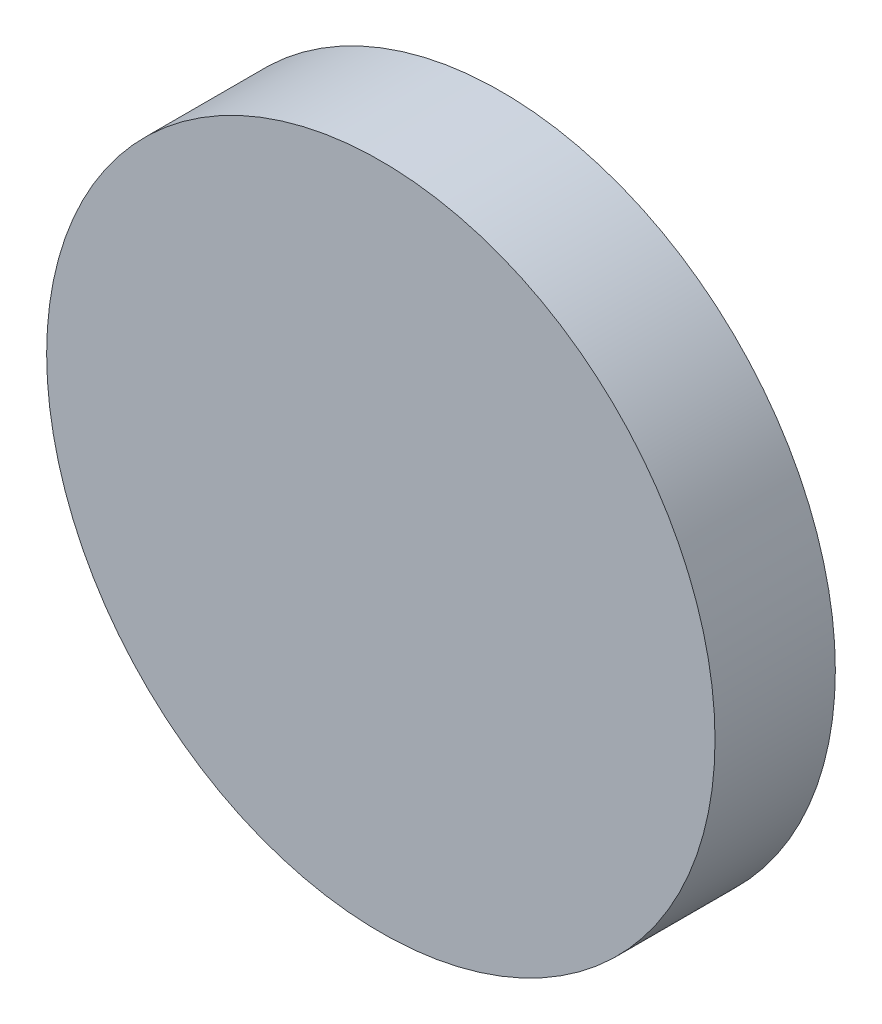
SolidWorks part; units mm, degrees
ref_plane "Front Plane" through (0, 0, 0) normal (0, 0, 1) x (1, 0, 0)
ref_plane "Top Plane" through (0, 0, 0) normal (0, 1, 0) x (1, 0, 0)
ref_plane "Right Plane" through (0, 0, 0) normal (1, 0, 0) x (0, 0, -1)
sketch "Sketch1" plane through (0, 0, 0) normal (0, 0, 1) x (1, 0, 0)
  circle A0 centre (0, 0) radius 100
extrude "Boss-Extrude1" add sketch "Sketch1" along normal blind 36
sketch "Sketch2" plane through (0, 0, 0) normal (0, 0, 1) x (1, 0, 0)
  circle A0 centre (0, 0) radius 97
extrude "Cut-Extrude2" cut sketch "Sketch2" along normal blind 33
sketch "Sketch3" plane through (0, 0, 0) normal (0, 0, 1) x (1, 0, 0)
  line L1 (-98, -7) -> (-88, -7)
  line L2 (-98, -7) -> (-98, 7)
  line L3 (-98, 7) -> (-88, 7)
  line L4 (-88, -7) -> (-88, 7)
  circle A0 centre (110, 24.75) radius 1.75
  circle A1 centre (110, -24.75) radius 1.75
  circle A2 centre (110, 0) radius 7
extrude "Cut-Extrude4" cut sketch "Sketch3" along normal blind 4
sketch "Sketch4" plane through (0, 0, 0) normal (0, 0, 1) x (1, 0, 0)
  circle A0 centre (0, 0) radius 12
